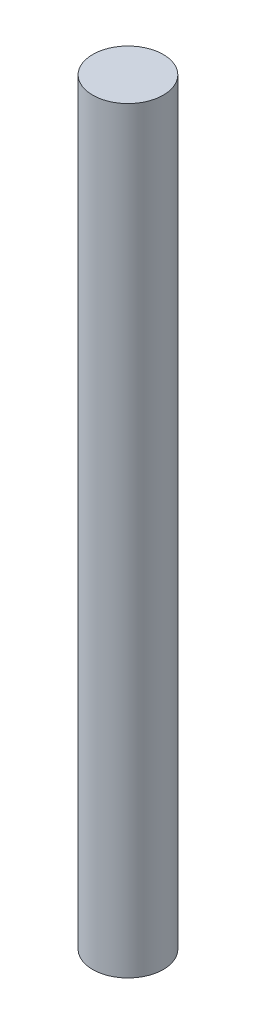
SolidWorks part; units mm, degrees
ref_plane "Front Plane" through (0, 0, 0) normal (0, 0, 1) x (1, 0, 0)
ref_plane "Top Plane" through (0, 0, 0) normal (0, 1, 0) x (1, 0, 0)
ref_plane "Right Plane" through (0, 0, 0) normal (1, 0, 0) x (0, 0, -1)
sketch "Sketch1" plane through (0, 0, 0) normal (0, 1, 0) x (1, 0, 0)
  circle A0 centre (0, 0) radius 1.5
  dimension "D1" = 3
extrude "Boss-Extrude1" add sketch "Sketch1" along normal blind 32.2
